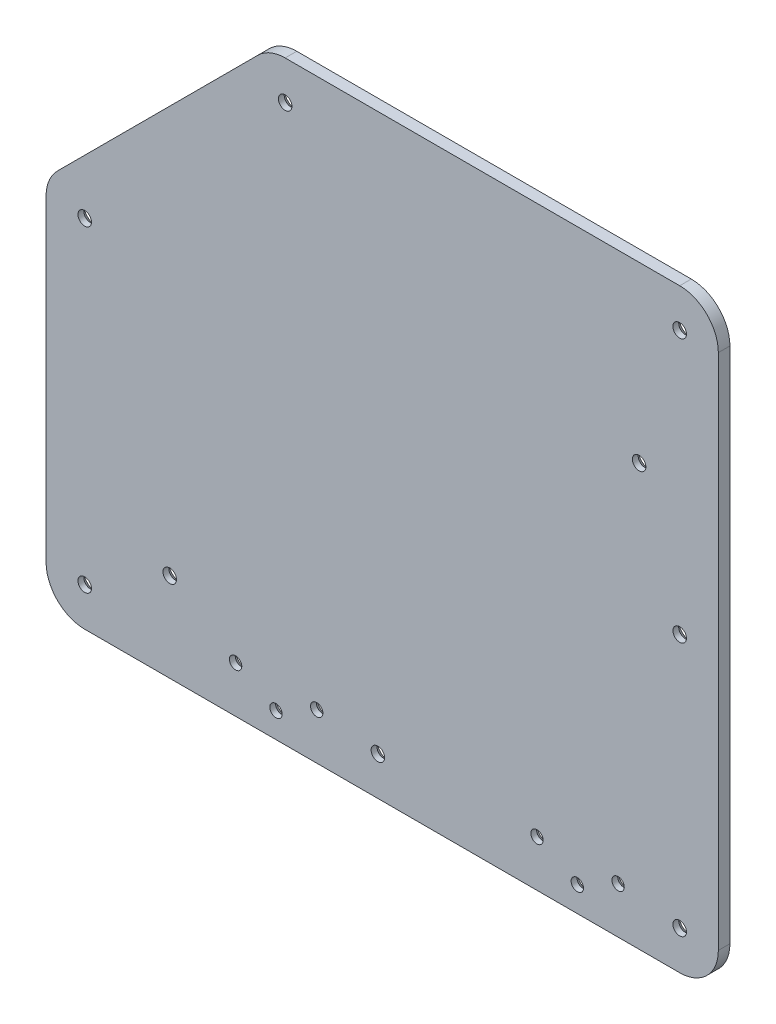
SolidWorks part; units mm, degrees
ref_plane "Piano frontale" through (0, 0, 0) normal (0, 0, 1) x (1, 0, 0)
ref_plane "Piano superiore" through (0, 0, 0) normal (0, 1, 0) x (1, 0, 0)
ref_plane "Piano destro" through (0, 0, 0) normal (1, 0, 0) x (0, 0, -1)
sketch "Schizzo1" plane through (0, 0, 0) normal (0, 0, 1) x (1, 0, 0)
  line L5 (0, 0) -> (170, 0) construction
  line L6 (170, 0) -> (170, 150) construction
  line L7 (170, 150) -> (56.5685, 150) construction
  line L8 (56.5685, 150) -> (0, 93.4315) construction
  line L9 (0, 93.4315) -> (0, 0) construction
  line L10 (172, 152) -> (55.7401, 152)
  line L11 (55.7401, 152) -> (-2, 94.2599)
  line L12 (-2, 94.2599) -> (-2, -2)
  line L13 (-2, -2) -> (172, -2)
  line L14 (172, -2) -> (172, 152)
  dimension "D5" = 2
  dimension "D1" = 150
  dimension "D2" = 80
  dimension "D3" = 170
  dimension "D4" = 135
extrude "Estrusione-Estrusione1" add sketch "Schizzo1" along normal blind 3
fillet "Raccordo1" radius 10 5 edges at (172, -2, 1.5) (-2, -2, 1.5) (55.7401, 152, 1.5) (172, 152, 1.5) (-2, 94.2599, 1.5)
sketch "Schizzo2" plane through (0, 0, 3) normal (0, 0, 1) x (1, 0, 0)
  circle A0 centre (162, 142) radius 1.75
  circle A1 centre (59.8823, 142) radius 1.75
  circle A2 centre (8, 90.1177) radius 1.75
  circle A3 centre (8, 8) radius 1.75
  circle A4 centre (162, 8) radius 1.75
  circle A5 centre (162, 73.8294) radius 1.75
  circle A6 centre (83.8818, 8) radius 1.75
  dimension "D1" = 3.5
extrude "Taglio-Estrusione1" cut sketch "Schizzo2" against normal blind 3
sketch "Schizzo3" plane through (0, 0, 3) normal (0, 0, 1) x (1, 0, 0)
  circle A2 centre (151.5, 107) radius 1.75
  circle A3 centre (30, 21) radius 1.75
  point P2 (0, 0)
  point P5 (0, 0)
  point P6 (151.5, 107)
  point P7 (151.5, 107)
  point P11 (0, 0)
  point P12 (30, 21)
  dimension "D1" = 3.5
extrude "Taglio-Estrusione2" cut sketch "Schizzo3" against normal blind 10
sketch "Schizzo6" plane through (0, 0, 3) normal (0, 0, 1) x (1, 0, 0)
  line L0 (8, -2) -> (162, -2) construction
  line L3 (-2, 90.1177) -> (-2, 8) construction
  line L7 (172, 8) -> (172, 142) construction
  line L8 (8, -2) -> (162, -2) construction
  circle A2 centre (57.5, 4.5) radius 1.6
  circle A3 centre (68.0536, 10) radius 1.6
  circle A4 centre (47.0536, 10) radius 1.6
  circle A8 centre (125.0536, 10) radius 1.6
  circle A9 centre (146.0536, 10) radius 1.6
  circle A10 centre (135.5, 4.5) radius 1.6
  dimension "D2" = 59.5
  dimension "D1" = 3.2
  dimension "D6" = 3.2
  dimension "D3" = 6.5
  dimension "D4" = 21
  dimension "D5" = 5.5
  dimension "D7" = 21
  dimension "D8" = 5.5
  dimension "D9" = 36.5
  dimension "D10" = 6.5
extrude "Taglio-Estrusione4" cut sketch "Schizzo6" against normal blind 10
chamfer "Smusso1" distance 1.5 angle 45 15 edges at (9.75, 8, 0) (85.6318, 8, 0) (163.75, 8, 0) (163.75, 73.8294, 0) (9.75, 90.1177, 0) (163.75, 142, 0) (61.6323, 142, 0) (31.75, 21, 0) (153.25, 107, 0) (48.6536, 10, 0) (59.1, 4.5, 0) (69.6536, 10, 0) (126.6536, 10, 0) (137.1, 4.5, 0) (147.6536, 10, 0)
